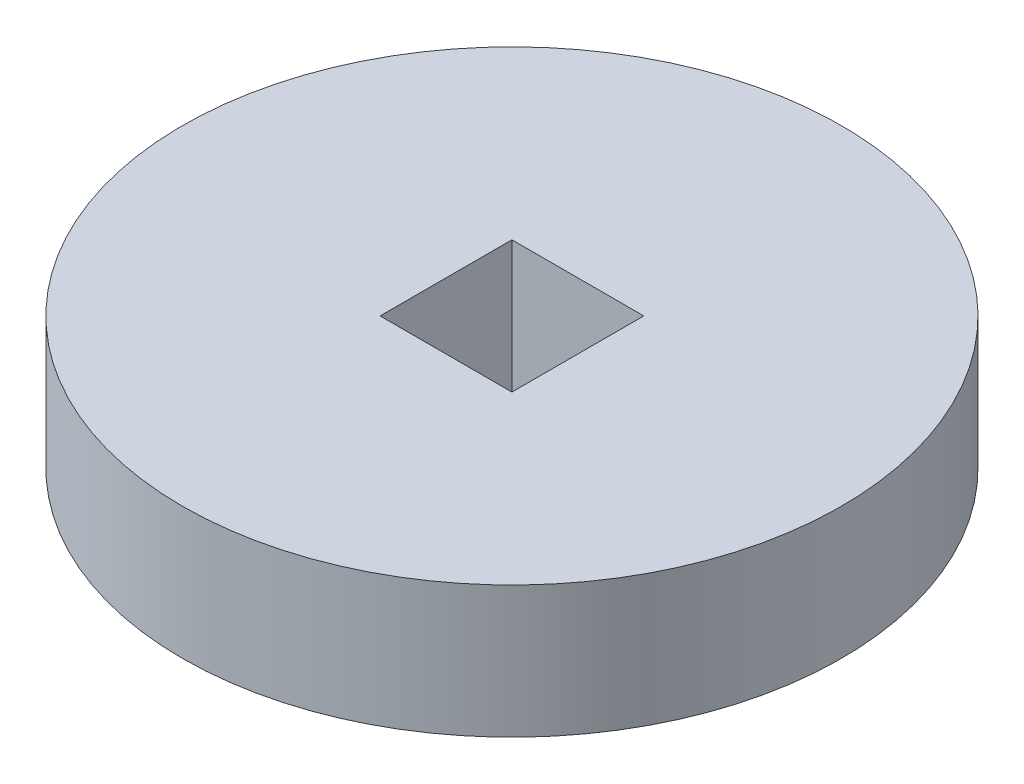
SolidWorks part; units mm, degrees
ref_plane "Front Plane" through (0, 0, 0) normal (0, 0, 1) x (1, 0, 0)
ref_plane "Top Plane" through (0, 0, 0) normal (0, 1, 0) x (1, 0, 0)
ref_plane "Right Plane" through (0, 0, 0) normal (1, 0, 0) x (0, 0, -1)
sketch "Elevator Support Pulleys" plane through (0, 0, 0) normal (0, 1, 0) x (1, 0, 0)
  line L1 (-3.175, 3.175) -> (3.175, 3.175)
  line L2 (-3.175, 3.175) -> (-3.175, -3.175)
  line L3 (-3.175, -3.175) -> (3.175, -3.175)
  line L4 (3.175, 3.175) -> (3.175, -3.175)
  line L5 (-3.175, 3.175) -> (3.175, -3.175) construction
  line L6 (-3.175, -3.175) -> (3.175, 3.175) construction
  circle A0 centre (0, 0) radius 15.875
  dimension "D1" = 31.75
  dimension "D2" = 6.35
  dimension "D3" = 6.35
extrude "Boss-Extrude1" add sketch "Elevator Support Pulleys" along normal blind 6.35
equation "\"Ball Diameter\"= 1.75in"
equation "\"Sheet Thickness\"= 0.25in"
equation "\"Screw Diameter\"= .17in"
equation "\"Robot Diameter\"= 16in"
equation "\"Castor Screw Diameter\"= 0.22in"
equation "\"Wheel Diameter\" = 4in"
equation "\"Nut Diameter\" = 8.4mm"
equation "\"Nut Height\" = 2.9mm"
equation "\"Screw Height\" = 0.55in"
equation "\"Pulley Diameter\" = 1in"
equation "\"Reactor Height\" = 14in"
equation "\"Elevator Height\" = 11.5in"
equation "\"Elevator Width\" = \"Ball Diameter\" + 0.25in"
equation "\"Elevator Axle Length\" = \"Elevator Width\" + 6*\"Sheet Thickness\""
equation "\"D1@Elevator Support Pulleys\"=\"Pulley Diameter\"+0.25in"
equation "\"D2@Elevator Support Pulleys\"=\"Sheet Thickness\""
equation "\"D3@Elevator Support Pulleys\"=\"Sheet Thickness\""
equation "\"D1@Boss-Extrude1\"=\"Sheet Thickness\""
